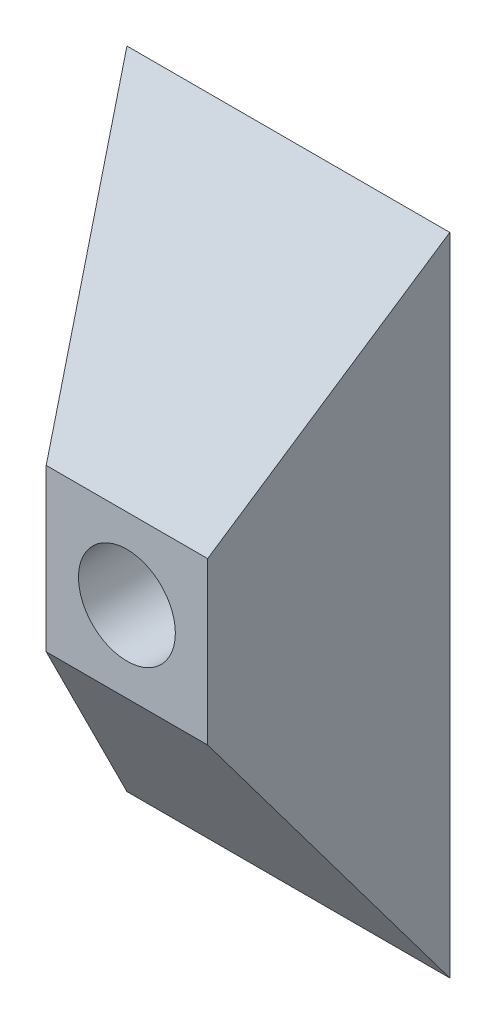
SolidWorks part; units mm, degrees
ref_plane "Alzado" through (0, 0, 0) normal (0, 0, 1) x (1, 0, 0)
ref_plane "Planta" through (0, 0, 0) normal (0, 1, 0) x (1, 0, 0)
ref_plane "Vista lateral" through (0, 0, 0) normal (1, 0, 0) x (0, 0, -1)
sketch "Croquis1" plane through (0, 0, 0) normal (0, 0, 1) x (1, 0, 0)
  line L1 (-5, -10) -> (5, -10)
  line L2 (-5, -10) -> (-5, 10)
  line L3 (-5, 10) -> (5, 10)
  line L4 (5, -10) -> (5, 10)
  line L5 (-5, -10) -> (5, 10) construction
  line L6 (-5, 10) -> (5, -10) construction
  point P0 (0, 0)
  dimension "D1" = 10
  dimension "D2" = 20
ref_plane "Plano1" through (0, 0, 5) normal (0, 0, 1) x (1, 0, 0)
sketch "Croquis9" plane through (0, 0, 5) normal (0, 0, 1) x (1, 0, 0)
  line L1 (-2.5, 2.5) -> (2.5, 2.5)
  line L2 (-2.5, 2.5) -> (-2.5, -2.5)
  line L3 (-2.5, -2.5) -> (2.5, -2.5)
  line L4 (2.5, 2.5) -> (2.5, -2.5)
  line L5 (-2.5, 2.5) -> (2.5, -2.5) construction
  line L6 (-2.5, -2.5) -> (2.5, 2.5) construction
  point P0 (0, 0)
  dimension "D1" = 5
loft "Recubrir1" add profiles "Croquis1", "Croquis9"
sketch "Croquis10" plane through (0, 0, 5) normal (0, 0, 1) x (1, 0, 0)
  circle A0 centre (0, 0) radius 1.5
  dimension "D1" = 3
extrude "Cortar-Extruir1" cut sketch "Croquis10" against normal blind 5
sketch "Croquis11" plane through (0, 0, 0) normal (0, 0, -1) x (-1, 0, 0)
  circle A0 centre (0, 0) radius 2.5
  dimension "D1" = 5
extrude "Cortar-Extruir2" cut sketch "Croquis11" against normal blind 2
